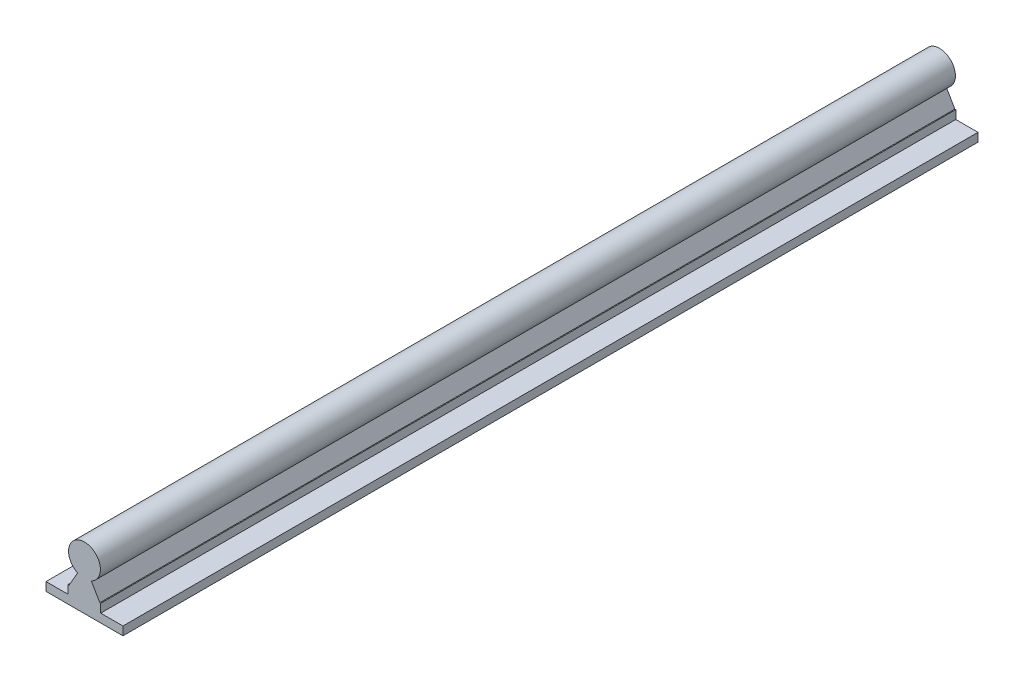
SolidWorks part; units mm, degrees
ref_plane "Front Plane" through (0, 0, 0) normal (0, 0, 1) x (1, 0, 0)
ref_plane "Top Plane" through (0, 0, 0) normal (0, 1, 0) x (1, 0, 0)
ref_plane "Right Plane" through (0, 0, 0) normal (1, 0, 0) x (0, 0, -1)
ref_plane "Plane1"
sketch "Sketch1" plane through (0, 0, 0) normal (0, 0, 1) x (1, 0, 0)
  line L0 (-22.5, 0) -> (22.5, 0)
  line L1 (22.5, 0) -> (22.5, 5)
  line L2 (22.5, 5) -> (9.5, 5)
  line L3 (9.5, 5) -> (9.5, 10)
  line L4 (9.5, 10) -> (8.9676, 10)
  line L5 (8.9676, 10) -> (4, 18.6042)
  line L6 (-4, 18.6042) -> (-8.9676, 10)
  line L7 (-8.9676, 10) -> (-9.5, 10)
  line L8 (-9.5, 10) -> (-9.5, 5)
  line L9 (-9.5, 5) -> (-22.5, 5)
  line L10 (-22.5, 5) -> (-22.5, 0)
  arc A0 (4, 18.6042) -> (-4, 18.6042) centre (0, 27) ccw
  dimension "D8" = 18.6
  dimension "D1" = 45
  dimension "D2" = 5
  dimension "D3" = 5
  dimension "D4" = 19
  dimension "D5" = 13
  dimension "D6" = 10
  dimension "D7" = 5
  dimension "D9" = 8
  dimension "D10" = 270
extrude "Extrusion1" add sketch "Sketch1" along normal blind 500
